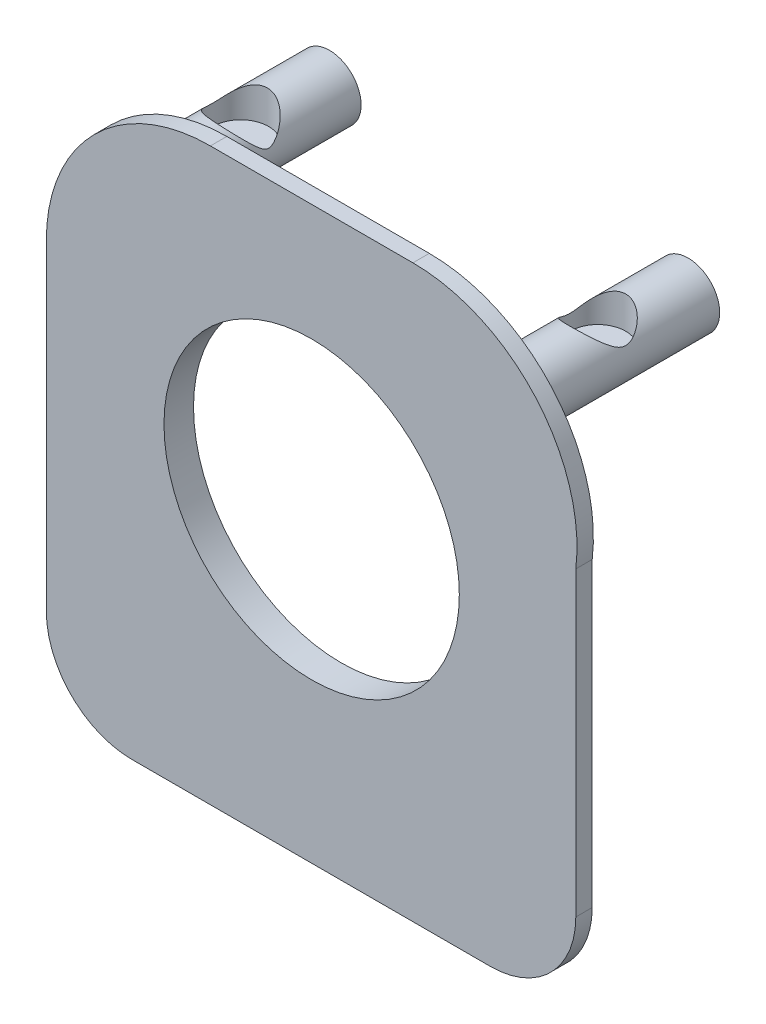
SolidWorks part; units mm, degrees
material "PET"
ref_plane "Piano frontale" through (0, 0, 0) normal (0, 0, 1) x (1, 0, 0)
ref_plane "Piano superiore" through (0, 0, 0) normal (0, 1, 0) x (1, 0, 0)
ref_plane "Piano destro" through (0, 0, 0) normal (1, 0, 0) x (0, 0, -1)
sketch "Schizzo1" plane through (0, 0, 0) normal (0, 0, 1) x (1, 0, 0)
  line L0 (-6.1713, 16.1) -> (6.1713, 16.1) construction
  line L1 (-6.1713, 16.1) -> (6.1713, 16.1)
  line L2 (-16.1713, 6.1) -> (-16.1713, -13.4632)
  line L3 (-10.9575, -18.677) -> (10.8862, -18.677)
  line L4 (16.1, -13.4632) -> (16.1, 4.9079)
  line L5 (-10.9107, 10.852) -> (-13.2424, 13.1711) construction
  line L6 (0, -15.3886) -> (-0.0357, -18.677) construction
  circle A0 centre (0, -15.3886) radius 1.25 construction
  circle A1 centre (0, 0) radius 12.1 construction
  circle A2 centre (-10.9107, 10.852) radius 1.25 construction
  circle A3 centre (10.9445, 10.818) radius 1.25 construction
  arc A4 (16.1, 4.9079) -> (6.1713, 16.1) centre (6.1713, 6.1) ccw construction
  arc A5 (-6.1713, 16.1) -> (-16.1713, 6.1) centre (-6.1713, 6.1) ccw construction
  circle A6 centre (0, -15.3886) radius 1.25
  circle A7 centre (0, 0) radius 12.1
  circle A8 centre (-10.9107, 10.852) radius 1.25
  circle A9 centre (10.9445, 10.818) radius 1.25
  arc A10 (16.1, 4.9079) -> (6.1713, 16.1) centre (6.1713, 6.1) ccw
  arc A11 (-6.1713, 16.1) -> (-16.1713, 6.1) centre (-6.1713, 6.1) ccw
  arc A12 (-16.1713, -13.4632) -> (-10.9575, -18.677) centre (-10.9575, -13.4632) ccw
  arc A13 (10.8862, -18.677) -> (16.1, -13.4632) centre (10.8862, -13.4632) ccw
  circle A14 centre (-10.9107, 10.852) radius 1.75
  circle A15 centre (10.9445, 10.818) radius 1.75
  circle A16 centre (0, -15.3886) radius 1.75
  dimension "D1" = 3.5
extrude "Estrusione-Estrusione1" add sketch "Schizzo1" along normal blind 1 contours L3 A13 L4 A10 L1 A11 L2 A12 A16 A15 A14 A7
sketch "Schizzo2" plane through (0, 0, 1) normal (0, 0, 1) x (1, 0, 0)
  circle A0 centre (0, 0) radius 9 construction
  circle A1 centre (0, 0) radius 9
  circle A2 centre (0, 0) radius 12.1 construction
  circle A3 centre (0, 0) radius 12.1
extrude "Estrusione-Estrusione2" add sketch "Schizzo2" against normal blind 1.8
sketch "Schizzo3" plane through (0, 0, 0) normal (0, 0, -1) x (-1, 0, 0)
  circle A0 centre (-10.9445, 10.818) radius 1.925
  circle A1 centre (10.9107, 10.852) radius 1.925
  circle A2 centre (0, -15.3886) radius 1.925
  dimension "D1" = 3.85
extrude "Estrusione-Estrusione3" add sketch "Schizzo3" along normal blind 11
ref_plane "Piano1" through (0, 12.777, 0) normal (0, 1, 0) x (1, 0, 0)
sketch "Schizzo4" plane through (0, 12.777, 0) normal (0, 1, 0) x (1, 0, 0)
  line L0 (-8.9857, 11) -> (-12.8357, 11) construction
  line L1 (-8.9857, 11) -> (-12.8357, 11)
  line L2 (-12.6607, 0) -> (-9.1607, 0) construction
  line L3 (-12.6607, 0) -> (-9.1607, 0)
  line L4 (-10.9107, 11) -> (-10.9107, 0)
  line L5 (9.1945, 0) -> (12.6945, 0) construction
  line L6 (12.8695, 11) -> (9.0195, 11) construction
  line L7 (9.1945, 0) -> (12.6945, 0)
  line L8 (12.8695, 11) -> (9.0195, 11)
  line L9 (10.9445, 11) -> (10.9445, 0)
  circle A0 centre (-10.7453, 5.4252) radius 1.7
  circle A1 centre (10.9445, 5.5) radius 1.7
  dimension "D1" = 3.4
extrude "Taglio-Estrusione1" cut sketch "Schizzo4" against normal blind 2 contours L4 A0 | L4 A0 | A1
sketch "Schizzo5" plane through (0, 0, -11) normal (0, 0, -1) x (-1, 0, 0)
  circle A0 centre (0, -15.3886) radius 1.925
extrude "Taglio-Estrusione2" cut sketch "Schizzo5" against normal blind 7.2
sketch "Schizzo6" plane through (0, 0, -3.8) normal (0, 0, -1) x (-1, 0, 0)
  circle A0 centre (0, -15.3886) radius 1.425
  dimension "D1" = 2.85
extrude "Estrusione-Estrusione4" add sketch "Schizzo6" along normal blind 3.4
sketch "Schizzo7" plane through (0, 0, -7.2) normal (0, 0, -1) x (-1, 0, 0)
  circle A0 centre (0, -15.3886) radius 1.925 construction
  circle A1 centre (0, -15.3886) radius 1.925
extrude "Estrusione-Estrusione5" add sketch "Schizzo7" along normal blind 3.8
